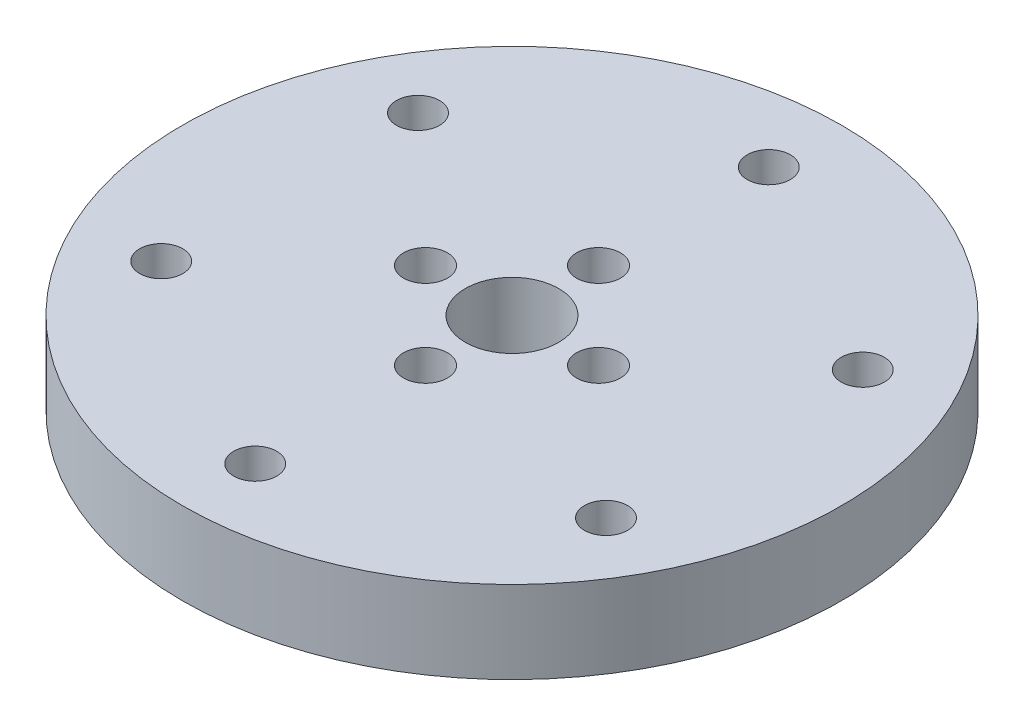
SolidWorks part; units mm, degrees
ref_plane "Front Plane" through (0, 0, 0) normal (0, 0, 1) x (1, 0, 0)
ref_plane "Top Plane" through (0, 0, 0) normal (0, 1, 0) x (1, 0, 0)
ref_plane "Right Plane" through (0, 0, 0) normal (1, 0, 0) x (0, 0, -1)
sketch "Sketch1" plane through (0, 0, 0) normal (0, 1, 0) x (1, 0, 0)
  circle A0 centre (0, 0) radius 30.48
  dimension "D1" = 60.96
extrude "Boss-Extrude1" add sketch "Sketch1" along normal blind 7.62 contours A0
sketch "Sketch2" plane through (0, 7.62, 0) normal (0, 1, 0) x (1, 0, 0)
  line L0 (0, 0) -> (0, -23.749)
  circle A0 centre (0, 0) radius 23.749
  circle A1 centre (0, -23.749) radius 1.9939
  dimension "D1" = 47.498
  dimension "D2" = 3.9878
extrude "Cut-Extrude1" cut sketch "Sketch2" against normal through all contours A1
pattern_circular "CirPattern1" count 6 over 360 about axis through (0, 0, 0) along (0, 1, 0) of "Cut-Extrude1"
sketch "Sketch3" plane through (0, 7.62, 0) normal (0, 1, 0) x (1, 0, 0)
  circle A0 centre (0, 0) radius 4.318
  circle A2 centre (0, -8.001) radius 2.032
  dimension "D1" = 8.636
  dimension "D3" = 4.064
extrude "Cut-Extrude2" cut sketch "Sketch3" against normal through all contours A0 | A2
pattern_circular "CirPattern2" count 4 over 360 about axis through (0, 0, 0) along (0, 1, 0) of "Cut-Extrude2"
